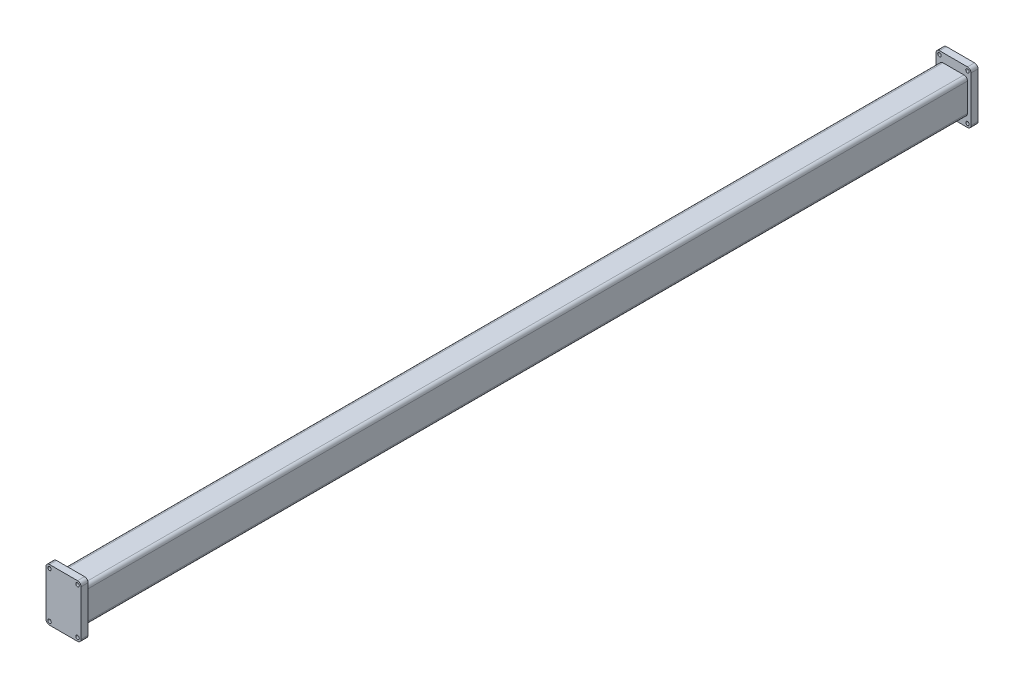
SolidWorks part; units mm, degrees
ref_plane "前视基准面" through (0, 0, 0) normal (0, 0, 1) x (1, 0, 0)
ref_plane "上视基准面" through (0, 0, 0) normal (0, 1, 0) x (1, 0, 0)
ref_plane "右视基准面" through (0, 0, 0) normal (1, 0, 0) x (0, 0, -1)
sketch "草图1" plane through (0, 0, 0) normal (0, 0, 1) x (1, 0, 0)
  line L1 (-4, 7.5) -> (4, 7.5)
  line L2 (-5, 6.5) -> (-5, -6.5)
  line L3 (-4, -7.5) -> (4, -7.5)
  line L4 (5, 6.5) -> (5, -6.5)
  arc A0 (4, -7.5) -> (5, -6.5) centre (4, -6.5) ccw
  arc A1 (-5, -6.5) -> (-4, -7.5) centre (-4, -6.5) ccw
  arc A2 (-4, 7.5) -> (-5, 6.5) centre (-4, 6.5) ccw
  arc A3 (5, 6.5) -> (4, 7.5) centre (4, 6.5) ccw
  circle A4 centre (4, 6.5) radius 0.5
  circle A5 centre (-4, 6.5) radius 0.5
  circle A6 centre (4, -6.5) radius 0.5
  circle A7 centre (-4, -6.5) radius 0.5
  dimension "D1" = 1
extrude "凸台-拉伸1" add sketch "草图1" along normal blind 2
sketch "草图2" plane through (0, 0, 0) normal (0, 0, -1) x (-1, 0, 0)
  line L1 (-3, 5) -> (3, 5)
  line L2 (-4, 4) -> (-4, -4)
  line L3 (-3, -5) -> (3, -5)
  line L4 (4, 4) -> (4, -4)
  arc A0 (-4, -4) -> (-3, -5) centre (-3, -4) ccw
  arc A1 (3, -5) -> (4, -4) centre (3, -4) ccw
  arc A2 (4, 4) -> (3, 5) centre (3, 4) ccw
  arc A3 (-4, 4) -> (-3, 5) centre (-3, 4) cw
  dimension "D1" = 1
extrude "拉伸-薄壁1" add sketch "草图2" along normal blind 126 thin
mirror "镜向1" about plane through (3, -4, -126) normal (0, 0, -1) of bodies 113
scale "缩放比例1" scale about origin uniform scaling yes scale factor 2
scale "缩放比例2" scale about origin uniform scaling yes scale factor 1.7
